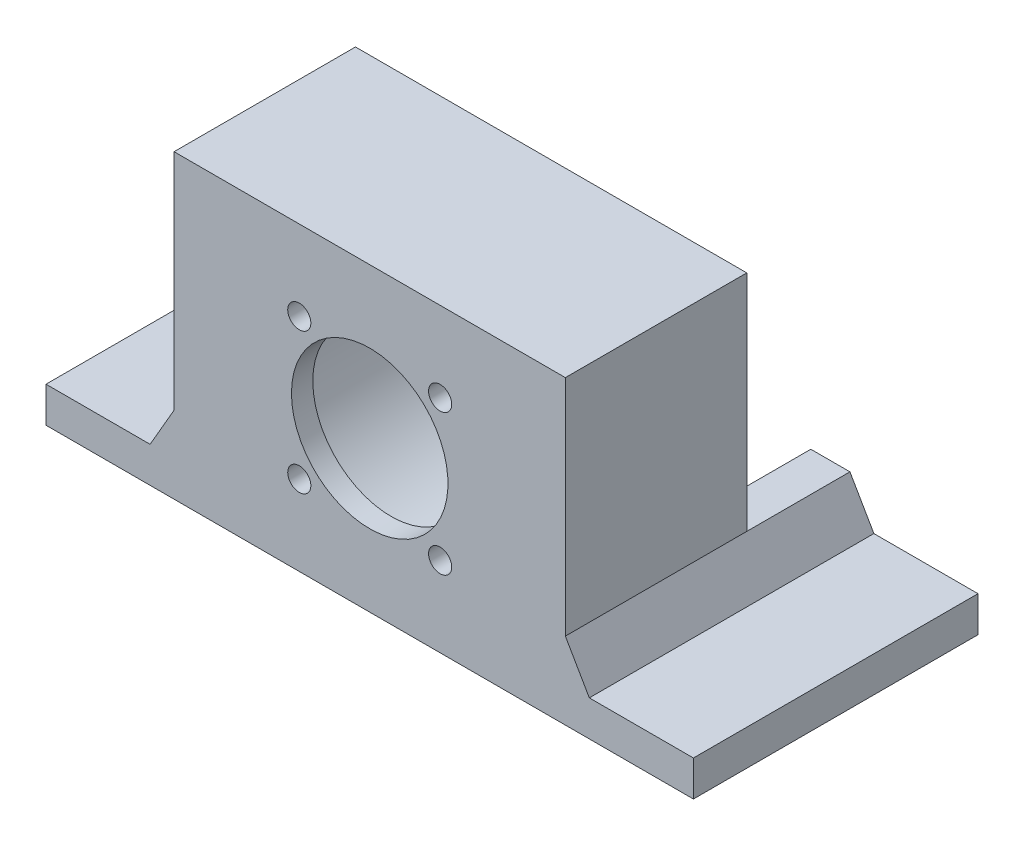
SolidWorks part; units mm, degrees
ref_plane "Plan de face" through (0, 0, 0) normal (0, 0, 1) x (1, 0, 0)
ref_plane "Plan de dessus" through (0, 0, 0) normal (0, 1, 0) x (1, 0, 0)
ref_plane "Plan de droite" through (0, 0, 0) normal (1, 0, 0) x (0, 0, -1)
sketch "Esquisse1" plane through (0, 0, 0) normal (0, 0, 1) x (1, 0, 0)
  line L1 (0, 0) -> (55, 0)
  line L2 (0, 0) -> (0, 42.3)
  line L3 (0, 42.3) -> (55, 42.3)
  line L4 (55, 0) -> (55, 42.3)
  dimension "D1" = 42.3
  dimension "D2" = 55
extrude "Boss.-Extru.1" add sketch "Esquisse1" along normal blind 25.5
sketch "Esquisse4" plane through (0, 0, 0) normal (0, 0, 1) x (1, 0, 0)
  line L1 (0, 0) -> (55, 0) construction
  line L5 (27.5, 42.3) -> (27.5, 0) construction
  line L6 (55, 42.3) -> (0, 42.3) construction
  circle A0 centre (27.5, 21.15) radius 18.1
  point P3 (27.5, 21.15)
  dimension "D1" = 36.2
extrude "Enlèv. mat.-Extru.3" cut sketch "Esquisse4" along normal offset from surface (22.5 mm away) 3 up to face at (27.5, 21.15, 25.5)
sketch "Esquisse5" plane through (37, 0, 25.5) normal (0, 0, -1) x (-1, 0, 0)
  circle A0 centre (9.5, 21.15) radius 11
  dimension "D1" = 22
extrude "Enlèv. mat.-Extru.4" cut sketch "Esquisse5" against normal through all and the other way through all
sketch "Esquisse6" plane through (0, 0, 25.5) normal (0, 0, -1) x (-1, 0, 0)
  line L0 (-27.5, 21.15) -> (-37.3995, 31.0495) construction
  line L2 (-38.5, 21.15) -> (-27.5, 21.15) construction
  circle A1 centre (-27.5, 21.15) radius 11 construction
  circle A2 centre (-37.3995, 31.0495) radius 1.625
  circle A3 centre (-27.5, 21.15) radius 14 construction
  circle A4 centre (-17.6005, 31.0495) radius 1.625
  circle A5 centre (-27.5, 21.15) radius 14 construction
  circle A6 centre (-17.6005, 11.2505) radius 1.625
  circle A7 centre (-27.5, 21.15) radius 14 construction
  circle A8 centre (-37.3995, 11.2505) radius 1.625
  circle A9 centre (-27.5, 21.15) radius 14 construction
  point P9 (-27.5, 21.15)
  point P17 (-35.2782, 28.9282)
  point P22 (-27.5, 21.15)
  dimension "D1" = 28
  dimension "D2" = 3.25
  dimension "D3" = 45
  dimension "D4" = 4
extrude "Enlèv. mat.-Extru.5" cut sketch "Esquisse6" along normal blind 10
ref_plane "Plan1" through (0, 21.15, 0) normal (0, -1, 0) x (-1, 0, 0)
ref_plane "Plan2" through (27.5, 0, 0) normal (-1, 0, 0) x (0, 0, 1)
sketch "Esquisse7" plane through (0, 0, 25.5) normal (0, 0, 1) x (1, 0, 0)
  line L0 (55, 0) -> (73, 0)
  line L2 (55, 0) -> (55, 42.3) construction
  line L4 (55, 5) -> (73, 5) construction
  line L8 (73, 0) -> (73, 5)
  line L9 (73, 5) -> (58.3674, 5)
  line L11 (55, 10.8325) -> (55, 0)
  line L12 (27.5, 14.025) -> (27.5, -14.025) construction
  line L17 (55, 10.8325) -> (58.3674, 5)
  line L18 (-18, 0) -> (-18, 5)
  line L19 (0, 0) -> (-18, 0)
  line L20 (-18, 5) -> (-3.3674, 5)
  line L21 (0, 10.8325) -> (-3.3674, 5)
  line L22 (0, 10.8325) -> (0, 0)
  dimension "D1" = 18
  dimension "D2" = 5
  dimension "D3" = 30
  dimension "D4" = 5.8325
extrude "Boss.-Extru.2" add sketch "Esquisse7" against normal blind 40
sketch "Esquisse16" plane through (0, 0, 0) normal (0, 0, -1) x (-1, 0, 0)
  line L2 (0, 0) -> (-55, 0) construction
  line L3 (0, 10.8325) -> (-5.5, 10.8325)
  line L4 (-5.5, 10.8325) -> (-5.5, 0)
  line L5 (-27.5, 41.9209) -> (-27.5, -9.8537) construction
  line L6 (-55, 0) -> (-55, 10.8325)
  line L7 (-27.5, -14.025) -> (-27.5, 14.025) construction
  line L10 (-5.5, 0) -> (0, 0)
  line L11 (0, 0) -> (0, 10.8325)
  line L12 (-49.5, 0) -> (-55, 0)
  line L13 (-49.5, 10.8325) -> (-49.5, 0)
  line L14 (-55, 10.8325) -> (-49.5, 10.8325)
  dimension "D1" = 44
extrude "Boss.-Extru.4" add sketch "Esquisse16" along normal up to surface (14.5 mm away) up to face at (62.8735, 4.1665, -14.5)
